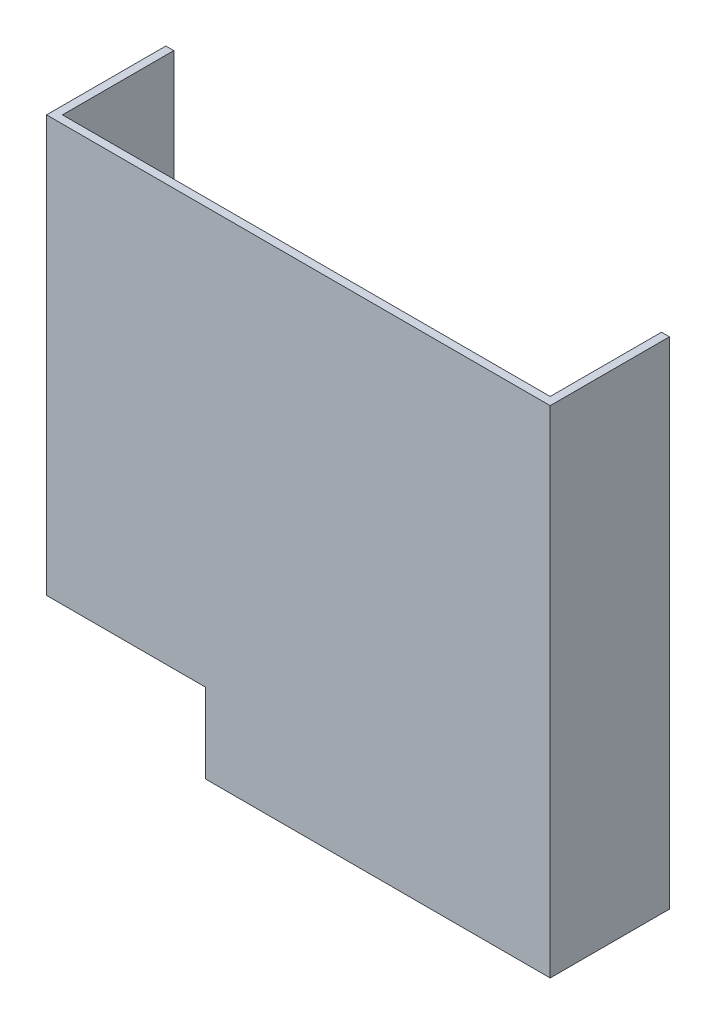
SolidWorks part; units mm, degrees
ref_plane "Alzado" through (0, 0, 0) normal (0, 0, 1) x (1, 0, 0)
ref_plane "Planta" through (0, 0, 0) normal (0, 1, 0) x (1, 0, 0)
ref_plane "Vista lateral" through (0, 0, 0) normal (1, 0, 0) x (0, 0, -1)
sketch "Croquis1" plane through (0, 0, 0) normal (0, 0, 1) x (1, 0, 0)
  line L1 (-38.0674, 29.152) -> (151.9326, 29.152)
  line L2 (-38.0674, 29.152) -> (-38.0674, -160.848)
  line L3 (-38.0674, -160.848) -> (151.9326, -160.848)
  line L4 (151.9326, 29.152) -> (151.9326, -160.848)
  dimension "D1" = 190
  dimension "D2" = 190
extrude "Saliente-Extruir1" add sketch "Croquis1" against normal blind 45
shell "Vaciado1" thickness 3
sketch "Croquis4" plane through (0, 0, 0) normal (0, 0, 1) x (1, 0, 0)
  line L1 (21.9326, -130.848) -> (-38.0674, -130.848)
  line L2 (21.9326, -130.848) -> (21.9326, -160.848)
  line L3 (21.9326, -160.848) -> (-38.0674, -160.848)
  line L4 (-38.0674, -130.848) -> (-38.0674, -160.848)
  dimension "D1" = 60
  dimension "D2" = 30
extrude "Cortar-Extruir1" cut sketch "Croquis4" against normal through all
sketch "Croquis7" plane through (0, 29.152, 0) normal (0, 1, 0) x (1, 0, 0)
  line L1 (151.9326, 0) -> (-38.0674, 0)
  line L2 (151.9326, 0) -> (151.9326, 45)
  line L3 (151.9326, 45) -> (-38.0674, 45)
  line L4 (-38.0674, 0) -> (-38.0674, 45)
extrude "Cortar-Extruir2" cut sketch "Croquis7" against normal blind 3
